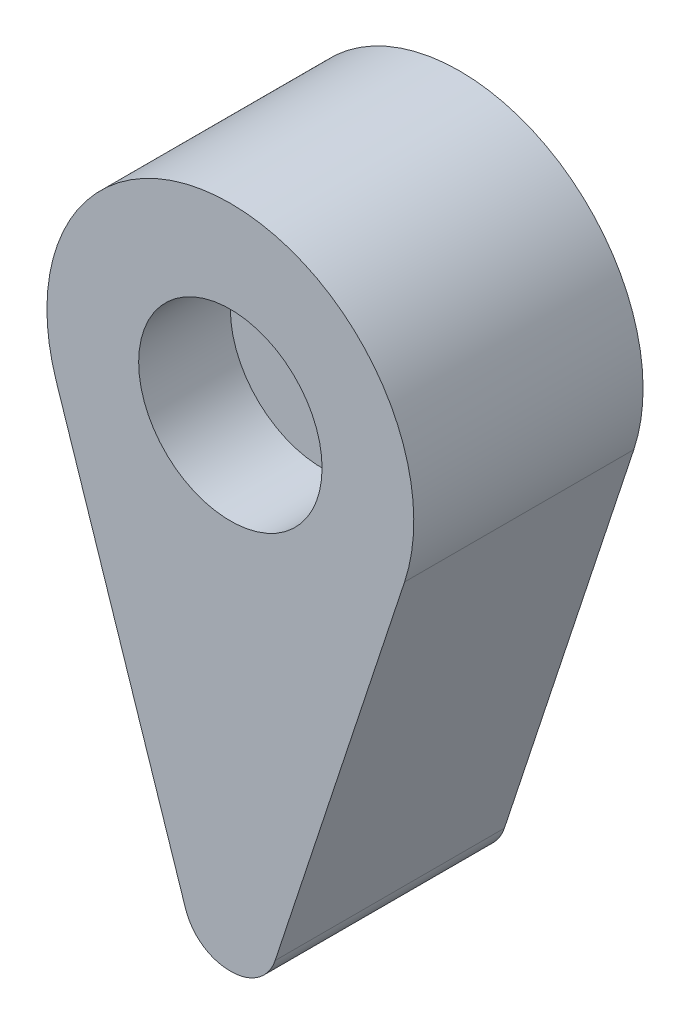
SolidWorks part; units mm, degrees
material "Сплав 2024"
ref_plane "Спереди" through (0, 0, 0) normal (0, 0, 1) x (1, 0, 0)
ref_plane "Сверху" through (0, 0, 0) normal (0, 1, 0) x (1, 0, 0)
ref_plane "Справа" through (0, 0, 0) normal (1, 0, 0) x (0, 0, -1)
sketch "Эскиз1" plane through (0, 0, 0) normal (0, 0, 1) x (1, 0, 0)
  line L0 (0, 18.3103) -> (0, -37.454) construction
  line L1 (-1.5, -21) -> (-7.5977, -2.5049)
  line L2 (1.5, -21) -> (7.5977, -2.5049)
  line L4 (-1.5, -21) -> (1.5, -21)
  arc A0 (7.5977, -2.5049) -> (-7.5977, -2.5049) centre (0, 0) ccw
  point P1 (0, -21)
  dimension "D1" = 16
  dimension "D2" = 3
  dimension "D3" = 21
extrude "Бобышка-Вытянуть1" add sketch "Эскиз1" along normal blind 10
hole_wizard "Цековка для винта с внутренним шестигранником M41" [suppressed] positions "Эскиз3" profile "Эскиз2" counterbore size "M4" standard "Ansi Metric"
sketch "Эскиз3" plane through (0, 10, 0) normal (0, 1, 0) x (1, 0, 0)
  point P0 (0, 0)
sketch "Эскиз2" plane through (0, 10, 0) normal (1, 0, 0) x (0, 0, 1)
  line L0 (0, 0) -> (0, 10)
  line L1 (0, 10) -> (2.25, 10)
  line L3 (2.25, 10) -> (2.25, 4)
  line L4 (2.25, 4) -> (4, 4)
  line L5 (4, 4) -> (4, 0)
  line L7 (4, 0) -> (0, 0)
  line L11 (0, -6.35) -> (0, 107.95) construction
  dimension "Диаметр сквозного отверстия" = 4.5
  dimension "Глубина сквозного отверстия" = 10
  dimension "Диаметр цековки" = 8
  dimension "Глубина цековки" = 4
fillet "Скругление1" radius 2 2 edges at (1.5, -21, 5) (-1.5, -21, 5)
fillet "Скругление2" [suppressed] radius 5
chamfer "Фаска1" [suppressed] distance 0.5 angle 45
sketch "Эскиз4" plane through (0, 0, 10) normal (0, 0, 1) x (1, 0, 0)
  circle A0 centre (0, 0) radius 4
  dimension "D1" = 8
extrude "Вырез-Вытянуть1" cut sketch "Эскиз4" against normal blind 4
hole_wizard "Отверстие обработанное метчиком M4x0.71" positions "Эскиз6" profile "Эскиз5" tap size "M4x0.7" standard "Ansi Metric" end condition through all
sketch "Эскиз6" plane through (0, 0, 6) normal (0, 0, 1) x (1, 0, 0)
  point P0 (0, 0)
sketch "Эскиз5" plane through (0, 0, 6) normal (1, 0, 0) x (0, -1, 0)
  line L0 (0, 0) -> (0, 6)
  line L1 (0, 6) -> (1.65, 6)
  line L2 (1.65, 6) -> (1.65, 0)
  line L5 (1.65, 0) -> (0, 0)
  line L11 (0, -6.35) -> (0, 107.95) construction
  dimension "Диаметр проходного сверла" = 3.3
  dimension "Глубина проходного сверла" = 6
cosmetic thread "Отверстие резьбы1" parameters "D2"=4
